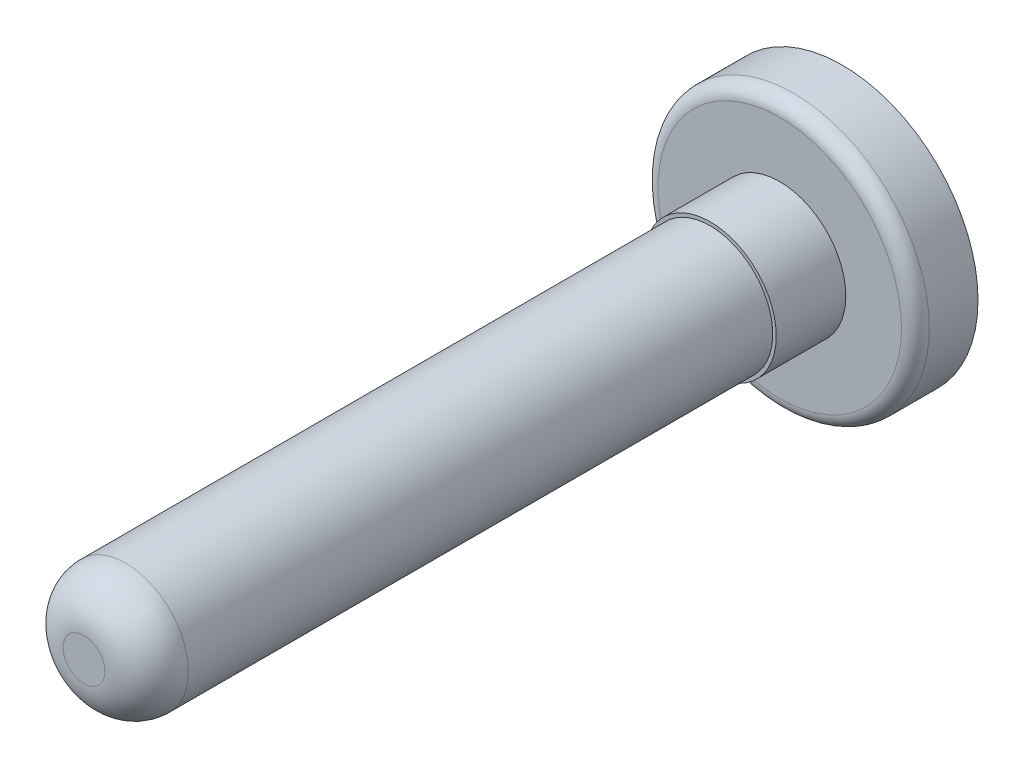
SolidWorks part; units mm, degrees
ref_plane "Front Plane" through (0, 0, 0) normal (0, 0, 1) x (1, 0, 0)
ref_plane "Top Plane" through (0, 0, 0) normal (0, 1, 0) x (1, 0, 0)
ref_plane "Right Plane" through (0, 0, 0) normal (1, 0, 0) x (0, 0, -1)
sketch "Sketch1" plane through (0, 0, 0) normal (0, 0, 1) x (1, 0, 0)
  circle A0 centre (0, 0) radius 10 construction
  circle A1 centre (0, 0) radius 9.75
  dimension "D1" = 20
  dimension "D2" = 19.5
extrude "Boss-Extrude1" add sketch "Sketch1" along normal blind 4.5
sketch "Sketch2" plane through (0, 0, 4.5) normal (0, 0, 1) x (1, 0, 0)
  circle A0 centre (0, 0) radius 5 construction
  circle A1 centre (0, 0) radius 4.75
  dimension "D1" = 9.5
  dimension "D2" = 10
extrude "Boss-Extrude2" add sketch "Sketch2" along normal blind 5
sketch "Sketch3" plane through (0, 0, 9.5) normal (0, 0, 1) x (1, 0, 0)
  circle A0 centre (0, 0) radius 5 construction
  circle A1 centre (0, 0) radius 4.5
  dimension "D1" = 10
  dimension "D2" = 9
extrude "Boss-Extrude3" add sketch "Sketch3" along normal blind 45 contours A1
fillet "Fillet3" radius 3 1 edges at (4.5, 0, 54.5)
fillet "Fillet4" radius 1 1 edges at (9.75, 0, 4.5)
